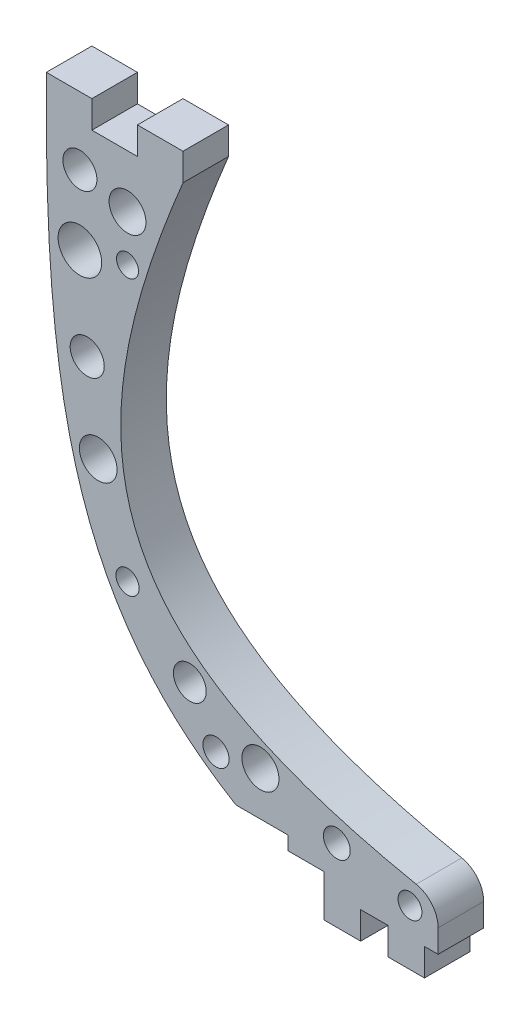
SolidWorks part; units mm, degrees
ref_plane "Plan de face" through (0, 0, 0) normal (0, 0, 1) x (1, 0, 0)
ref_plane "Plan de dessus" through (0, 0, 0) normal (0, 1, 0) x (1, 0, 0)
ref_plane "Plan de droite" through (0, 0, 0) normal (1, 0, 0) x (0, 0, -1)
sketch "Esquisse3" plane through (0, 0, 0) normal (0, 0, 1) x (1, 0, 0)
  line L0 (-7.5, 57.73) -> (-7.5, 0) construction
  line L1 (7.5, 57.73) -> (7.5, 17.9308) construction
  line L2 (30, -4.6) -> (30, -1.6)
  line L3 (34, -4.6) -> (30, -4.6)
  line L4 (30, -1.6) -> (27, -1.6)
  line L5 (27, -1.6) -> (27, -4.6)
  line L6 (27, 0) -> (-7.5, 0) construction
  line L7 (7.5, 17.9308) -> (35.5, 3.4) construction
  line L8 (34, -4.6) -> (34, -1.6)
  line L9 (34, -1.6) -> (35.5, -1.6)
  line L10 (35.5, -1.6) -> (35.5, 3.4)
  line L11 (27, -4.6) -> (23, -4.6)
  line L12 (16, 0) -> (-7.5, 12.1955) construction
  line L13 (-7.5, 12.1955) -> (-7.5, 57.73) construction
  line L14 (23, -4.6) -> (23, 0)
  line L15 (-7.5, 93.6282) -> (-7.5, 21.7981) construction
  line L16 (0.0112, 8.2975) -> (31.6545, -8.124) construction
  line L17 (23, 0) -> (16, 0)
  circle A0 centre (-3.8151, 53.3093) radius 1.8639
  circle A1 centre (1.412, 51.9307) radius 2.0235
  circle A2 centre (-3.8151, 45.6697) radius 2.394
  circle A3 centre (1.412, 46.8759) radius 1.2063
  circle A4 centre (-3.0109, 35.9622) radius 1.8701
  circle A5 centre (-1.8047, 26.8291) radius 2.0679
  circle A6 centre (1.412, 16.777) radius 1.2715
  circle A7 centre (8.2475, 10.6309) radius 1.7991
  circle A8 centre (11.1195, 5.4612) radius 1.436
  circle A9 centre (16, 6.3228) radius 2.0318
  circle A10 centre (24.3837, 3.4) radius 1.4725
  circle A11 centre (32.4136, 1.4916) radius 1.3116
  spline S0 degree 3 poles (16, 0) (-3.777, 10.2634) (-7.5, 27.8008) (-7.5, 57.73) knots 0 0 0 0 1 1 1 1
  spline S1 degree 3 poles (35.5, 3.4) (-1.7755, 10.2128) (-5.5671, 26.4267) (7.5, 57.73) knots 0 0 0 0 1 1 1 1
  line B0 (0, 57.73) -> (0, 44.4605) construction
  line B1 (0, 57.73) -> (2.5, 57.73)
  line B2 (2.5, 60.73) -> (7.5, 60.73)
  line B3 (7.5, 60.73) -> (7.5, 57.73)
  line B4 (2.5, 60.73) -> (2.5, 57.73)
  line B5 (0, 57.73) -> (-2.5, 57.73)
  line B6 (-2.5, 57.73) -> (-2.5, 60.73)
  line B7 (-2.5, 60.73) -> (-7.5, 60.73)
  line B8 (-7.5, 60.73) -> (-7.5, 57.73)
  dimension "D9" = 1.6
  dimension "D1" = 3
  dimension "D2" = 4
  dimension "D3" = 1.5
  dimension "D4" = 3
  dimension "D5" = 1.6
  dimension "D6" = 5
  dimension "D7" = 30
  dimension "D8" = 12
  dimension "D10" = 57.73
sketch_block_instance "Insert M3 plots ep 5mm-3"
sketch_block "Insert M3 plots ep 5mm" parameters "D1"=5, "D2"=5, "D3"=3
extrude "Boss.-Extru.1" add sketch "Esquisse3" along normal blind 5
sketch "Esquisse4" plane through (0, 0, 5) normal (0, 0, 1) x (1, 0, 0)
  line L0 (23, 0) -> (16, 0) construction
  line L1 (19, 0) -> (13.3097, 0)
  line L2 (19, 0) -> (19, 1.5)
  line L3 (19, 1.5) -> (13.3097, 1.5)
  line L4 (13.3097, 0) -> (13.3097, 1.5)
  line L5 (23, -4.6) -> (23, 0) construction
  spline S0 degree 3 poles (16, 0) (-3.777, 10.2634) (-7.5, 27.8008) (-7.5, 57.73) knots 0 0 0 0 1 1 1 1 construction
  dimension "D1" = 1.5
  dimension "D2" = 4
extrude "Enlèv. mat.-Extru.1" cut sketch "Esquisse4" against normal through all
fillet "Congé1" radius 3 1 edges at (35.5, 3.4, 2.5)
